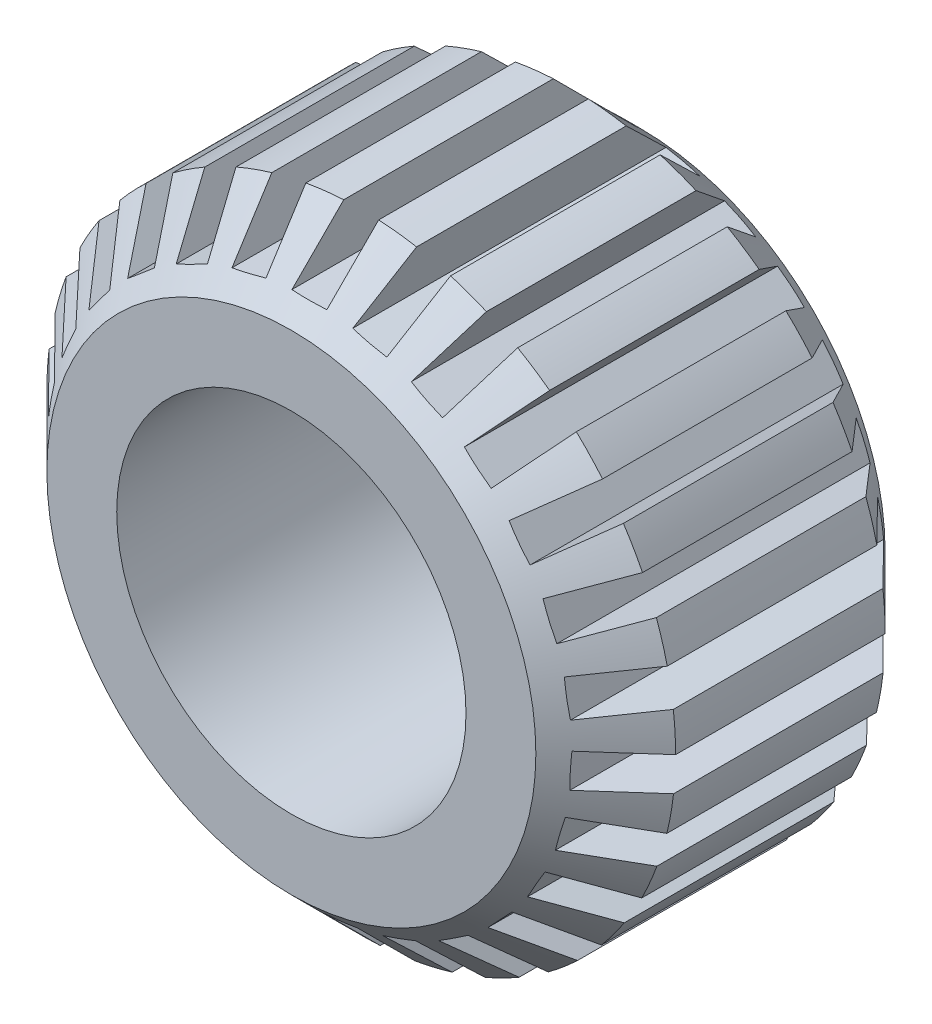
SolidWorks part; units mm, degrees
ref_plane "Front Plane" through (0, 0, 0) normal (0, 0, 1) x (1, 0, 0)
ref_plane "Top Plane" through (0, 0, 0) normal (0, 1, 0) x (1, 0, 0)
ref_plane "Right Plane" through (0, 0, 0) normal (1, 0, 0) x (0, 0, -1)
sketch "Sketch1" plane through (0, 0, 0) normal (0, 0, 1) x (1, 0, 0)
  circle A0 centre (0, 0) radius 5
  circle A1 centre (0, 0) radius 9
  dimension "D1" = 10
  dimension "D2" = 4
extrude "Boss-Extrude1" add sketch "Sketch1" along normal blind 10
chamfer "Chamfer1" distance 2 angle 45 2 edges at (9, 0, 0) (9, 0, 10)
sketch "Sketch2" plane through (0, 0, 0) normal (0, 0, 1) x (1, 0, 0)
  line L0 (0, 0) -> (0, 9) construction
  line L1 (0.5, 7.5) -> (0.5, 9)
  line L2 (-0.5, 7.5) -> (-0.5, 9)
  line L3 (-0.5, 7.5) -> (0.5, 7.5)
  line L5 (0.5, 0) -> (0.5, 9) construction
  line L6 (-0.5, 0) -> (-0.5, 9) construction
  circle A0 centre (0, 0) radius 9 construction
  arc A1 (0.5, 8.9861) -> (-0.5, 8.9861) centre (0, 0) ccw
  dimension "D3" = 7.5
  dimension "D1" = 0.5
  dimension "D2" = 0.5
extrude "Cut-Extrude1" cut sketch "Sketch2" along normal through all contours L1 A1 L2 L3
pattern_circular "CirPattern1" count 27 over 360 about axis through (0, 0, 0) along (0, 0, 1) of "Cut-Extrude1"
